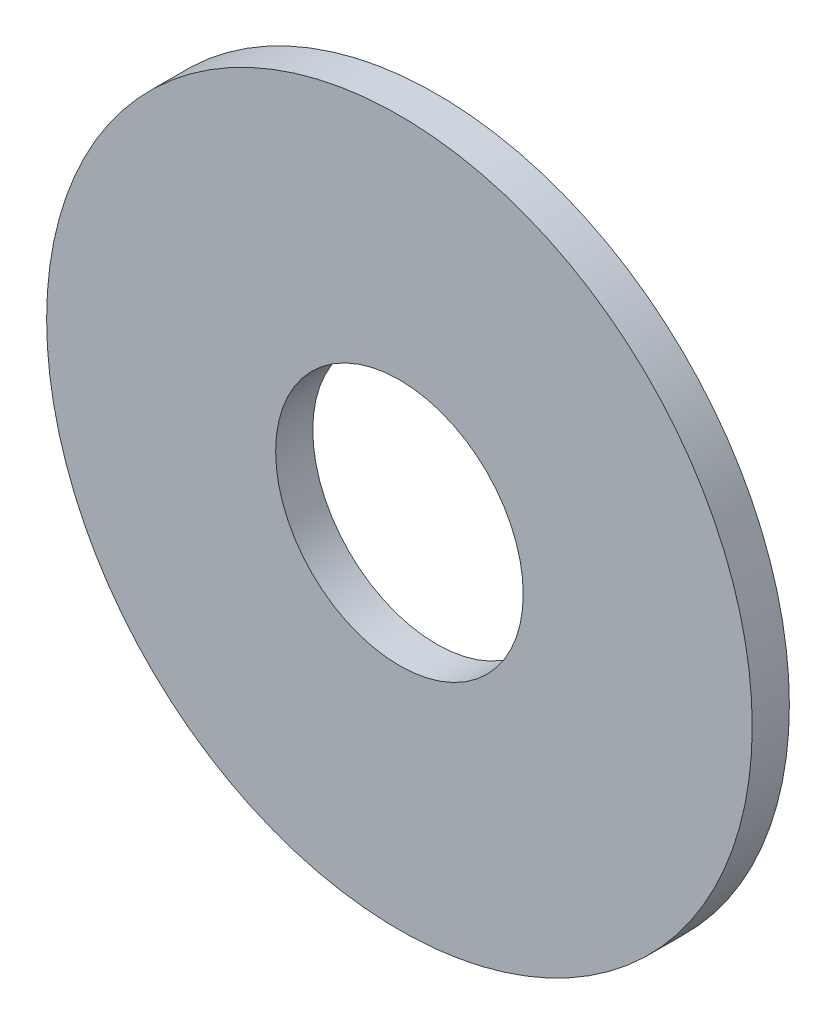
SolidWorks part; units mm, degrees
ref_plane "Front Plane" through (0, 0, 0) normal (0, 0, 1) x (1, 0, 0)
ref_plane "Top Plane" through (0, 0, 0) normal (0, 1, 0) x (1, 0, 0)
ref_plane "Right Plane" through (0, 0, 0) normal (1, 0, 0) x (0, 0, -1)
sketch "Sketch1" plane through (0, 0, 0) normal (0, 0, 1) x (1, 0, 0)
  circle A0 centre (0, 0) radius 2.54
  circle A1 centre (0, 0) radius 7.239
  dimension "ID" = 5.08
  dimension "OD" = 14.478
extrude "Extrude1" add sketch "Sketch1" against normal blind 0.762
